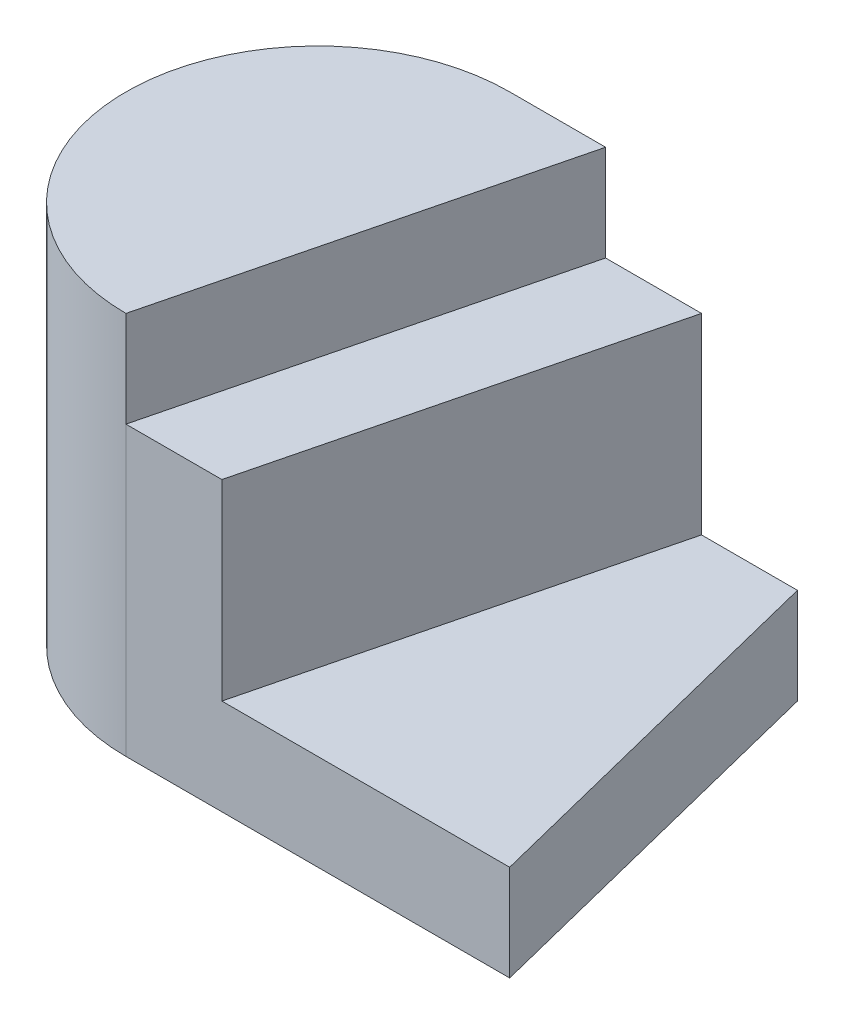
SolidWorks part; units mm, degrees
ref_plane "Front Plane" through (0, 0, 0) normal (0, 0, 1) x (1, 0, 0)
ref_plane "Top Plane" through (0, 0, 0) normal (0, 1, 0) x (1, 0, 0)
ref_plane "Right Plane" through (0, 0, 0) normal (1, 0, 0) x (0, 0, -1)
sketch "Sketch1" plane through (0, 0, 0) normal (0, 1, 0) x (1, 0, 0)
  line L0 (0, 0) -> (-10, 40)
  line L1 (-10, 40) -> (-40, 40)
  line L2 (0, 0) -> (-40, 0)
  arc A0 (-40, 40) -> (-40, 0) centre (-40, 20) ccw
  dimension "D2" = 30
  dimension "D1" = 40
  dimension "D3" = 40
extrude "Boss-Extrude1" add sketch "Sketch1" along normal blind 10
sketch "Sketch2" plane through (0, 10, 0) normal (0, 1, 0) x (1, 0, 0)
  line L0 (-10, 40) -> (-20, 40) construction
  line L1 (-10, 40) -> (-40, 40) construction
  line L2 (-40, 40) -> (-30, 40) construction
  line L3 (-30, 40) -> (-40, 0)
  line L4 (-40, 0) -> (-30, 0)
  line L5 (-40, 0) -> (0, 0) construction
  line L6 (-30, 0) -> (-20, 40)
  line L7 (-20, 40) -> (-30, 40)
  dimension "D1" = 10
  dimension "D2" = 10
extrude "Boss-Extrude2" add sketch "Sketch2" along normal blind 20
sketch "Sketch3" plane through (0, 10, 0) normal (0, 1, 0) x (1, 0, 0)
  line L0 (-30, 40) -> (-40, 0)
  line L1 (-30, 40) -> (-40, 40)
  arc A0 (-40, 40) -> (-40, 0) centre (-40, 20) ccw
extrude "Boss-Extrude3" add sketch "Sketch3" along normal blind 30
